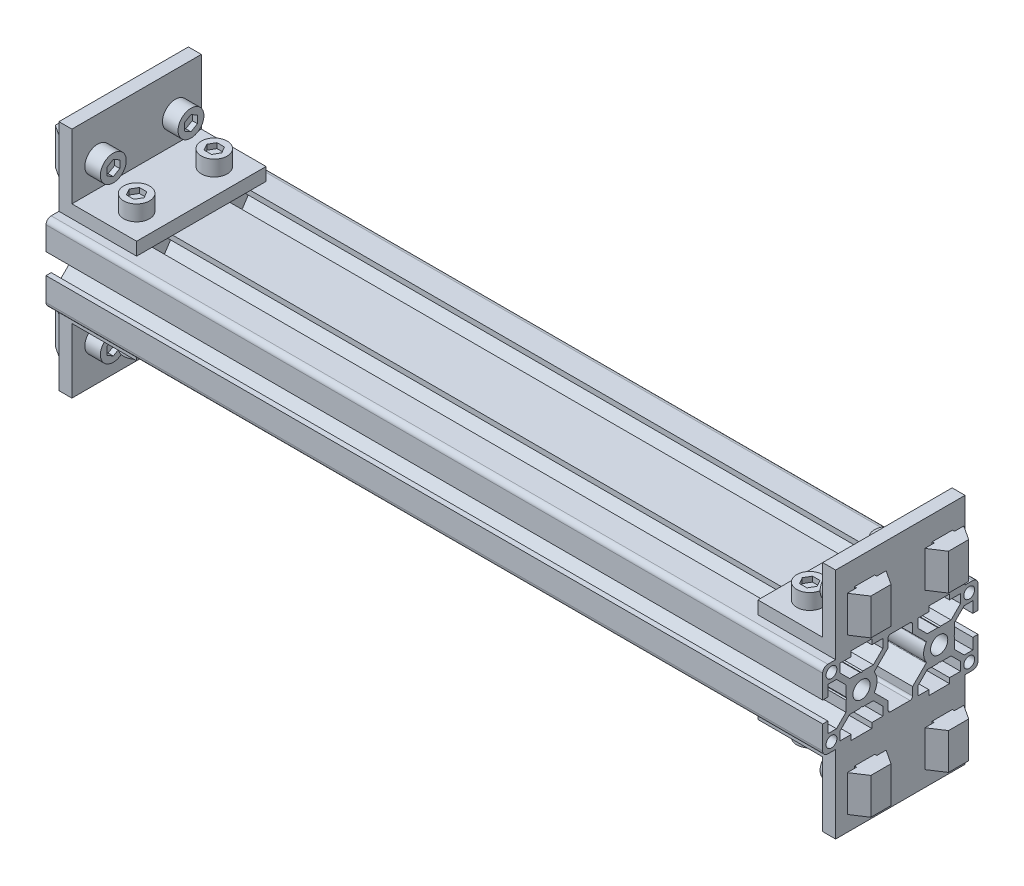
SolidWorks part; units mm, degrees
ref_plane "Front Plane" through (0, 0, 0) normal (0, 0, 1) x (1, 0, 0)
ref_plane "Top Plane" through (0, 0, 0) normal (0, 1, 0) x (1, 0, 0)
ref_plane "Right Plane" through (0, 0, 0) normal (1, 0, 0) x (0, 0, -1)
ref_plane "Plane1" through (300, 0, 0) normal (1, 0, 0) x (0, 0, -1)
ref_plane "Plane2" through (150, 0, 0) normal (1, 0, 0) x (0, 0, -1)
sketch "Sketch1" plane through (0, 0, 0) normal (1, 0, 0) x (0, 0, -1)
  line L0 (4.75, 8.8358) -> (4.75, 12)
  line L1 (3.75, 13) -> (-3.75, 13)
  line L2 (-4.75, 12) -> (-4.75, 8.8358)
  line L3 (-4.75, 8.8358) -> (-9.934, 3.6518)
  line L4 (-9.934, -3.6518) -> (-4.75, -8.8358)
  line L5 (-4.75, -8.8358) -> (-4.75, -12)
  line L6 (-3.75, -13) -> (3.75, -13)
  line L7 (4.75, -12) -> (4.75, -8.8358)
  line L8 (4.75, -8.8358) -> (9.934, -3.6518)
  line L9 (9.934, 3.6518) -> (4.75, 8.8358)
  line L10 (-11, -15) -> (11, -15)
  line L11 (11, -15) -> (11, -13)
  line L12 (11, -13) -> (6.75, -13)
  line L13 (6.75, -13) -> (6.75, -9.6642)
  line L14 (6.75, -9.6642) -> (10.4142, -6)
  line L15 (10.4142, -6) -> (14.4804, -6)
  line L16 (14.4804, -6) -> (15, -5.7)
  line L17 (15, -5.7) -> (15.5196, -6)
  line L18 (15.5196, -6) -> (19.5858, -6)
  line L19 (19.5858, -6) -> (23.25, -9.6642)
  line L20 (23.25, -9.6642) -> (23.25, -13)
  line L21 (23.25, -13) -> (19, -13)
  line L22 (19, -13) -> (19, -15)
  line L23 (19, -15) -> (28, -15)
  line L24 (30, -13) -> (30, -4)
  line L25 (30, -4) -> (28, -4)
  line L26 (28, -4) -> (28, -8.25)
  line L27 (28, -8.25) -> (24.6642, -8.25)
  line L28 (24.6642, -8.25) -> (21, -4.5858)
  line L29 (21, -4.5858) -> (21, -0.5196)
  line L30 (21, -0.5196) -> (20.7, 0)
  line L31 (20.7, 0) -> (21, 0.5196)
  line L32 (21, 0.5196) -> (21, 4.5858)
  line L33 (21, 4.5858) -> (24.6642, 8.25)
  line L34 (24.6642, 8.25) -> (28, 8.25)
  line L35 (28, 8.25) -> (28, 4)
  line L36 (28, 4) -> (30, 4)
  line L37 (30, 4) -> (30, 13)
  line L38 (28, 15) -> (19, 15)
  line L39 (19, 15) -> (19, 13)
  line L40 (19, 13) -> (23.25, 13)
  line L41 (23.25, 13) -> (23.25, 9.6642)
  line L42 (23.25, 9.6642) -> (19.5858, 6)
  line L43 (19.5858, 6) -> (15.5196, 6)
  line L44 (15.5196, 6) -> (15, 5.7)
  line L45 (15, 5.7) -> (14.4804, 6)
  line L46 (14.4804, 6) -> (10.4142, 6)
  line L47 (10.4142, 6) -> (6.75, 9.6642)
  line L48 (6.75, 9.6642) -> (6.75, 13)
  line L49 (6.75, 13) -> (11, 13)
  line L50 (11, 13) -> (11, 15)
  line L51 (11, 15) -> (-11, 15)
  line L52 (-11, 15) -> (-11, 13)
  line L53 (-11, 13) -> (-6.75, 13)
  line L54 (-6.75, 13) -> (-6.75, 9.6642)
  line L55 (-6.75, 9.6642) -> (-10.4142, 6)
  line L56 (-10.4142, 6) -> (-14.4804, 6)
  line L57 (-14.4804, 6) -> (-15, 5.7)
  line L58 (-15, 5.7) -> (-15.5196, 6)
  line L59 (-15.5196, 6) -> (-19.5858, 6)
  line L60 (-19.5858, 6) -> (-23.25, 9.6642)
  line L61 (-23.25, 9.6642) -> (-23.25, 13)
  line L62 (-23.25, 13) -> (-19, 13)
  line L63 (-19, 13) -> (-19, 15)
  line L64 (-19, 15) -> (-28, 15)
  line L65 (-30, 13) -> (-30, 4)
  line L66 (-30, 4) -> (-28, 4)
  line L67 (-28, 4) -> (-28, 8.25)
  line L68 (-28, 8.25) -> (-24.6642, 8.25)
  line L69 (-24.6642, 8.25) -> (-21, 4.5858)
  line L70 (-21, 4.5858) -> (-21, 0.5196)
  line L71 (-21, 0.5196) -> (-20.7, 0)
  line L72 (-20.7, 0) -> (-21, -0.5196)
  line L73 (-21, -0.5196) -> (-21, -4.5858)
  line L74 (-21, -4.5858) -> (-24.6642, -8.25)
  line L75 (-24.6642, -8.25) -> (-28, -8.25)
  line L76 (-28, -8.25) -> (-28, -4)
  line L77 (-28, -4) -> (-30, -4)
  line L78 (-30, -4) -> (-30, -13)
  line L79 (-28, -15) -> (-19, -15)
  line L80 (-19, -15) -> (-19, -13)
  line L81 (-19, -13) -> (-23.25, -13)
  line L82 (-23.25, -13) -> (-23.25, -9.6642)
  line L83 (-23.25, -9.6642) -> (-19.5858, -6)
  line L84 (-19.5858, -6) -> (-15.5196, -6)
  line L85 (-15.5196, -6) -> (-15, -5.7)
  line L86 (-15, -5.7) -> (-14.4804, -6)
  line L87 (-14.4804, -6) -> (-10.4142, -6)
  line L88 (-10.4142, -6) -> (-6.75, -9.6642)
  line L89 (-6.75, -9.6642) -> (-6.75, -13)
  line L90 (-6.75, -13) -> (-11, -13)
  line L91 (-11, -13) -> (-11, -15)
  line L92 (0, 15) -> (0, -15) construction
  arc A0 (28, -15) -> (30, -13) centre (28, -13) ccw
  arc A1 (30, 13) -> (28, 15) centre (28, 13) ccw
  arc A2 (-28, 15) -> (-30, 13) centre (-28, 13) ccw
  arc A3 (-30, -13) -> (-28, -15) centre (-28, -13) ccw
  circle A4 centre (-26.6, -11.6) radius 2.1
  circle A5 centre (-26.6, 11.6) radius 2.1
  circle A6 centre (-15, 0) radius 3.3235
  circle A7 centre (26.6, -11.6) radius 2.1
  circle A8 centre (15, 0) radius 3.3235
  circle A9 centre (26.6, 11.6) radius 2.1
  arc A10 (4.75, 12) -> (3.75, 13) centre (3.75, 12) ccw
  arc A11 (-3.75, 13) -> (-4.75, 12) centre (-3.75, 12) ccw
  arc A12 (-9.934, 3.6518) -> (-9.9732, 3.2759) centre (-9.7219, 3.4397) ccw
  arc A13 (-9.9732, -3.2759) -> (-9.9732, 3.2759) centre (-15, 0) ccw
  arc A14 (-9.9732, -3.2759) -> (-9.934, -3.6518) centre (-9.7219, -3.4397) ccw
  arc A15 (-4.75, -12) -> (-3.75, -13) centre (-3.75, -12) ccw
  arc A16 (3.75, -13) -> (4.75, -12) centre (3.75, -12) ccw
  arc A17 (9.934, -3.6518) -> (9.9732, -3.2759) centre (9.7219, -3.4397) ccw
  arc A18 (9.9732, 3.2759) -> (9.9732, -3.2759) centre (15, 0) ccw
  arc A19 (9.9732, 3.2759) -> (9.934, 3.6518) centre (9.7219, 3.4397) ccw
  point P106 (0, 0)
extrude "Boss-Extrude1" add sketch "Sketch1" along normal up to surface (300 mm away) up to plane "Plane1"
sketch "Sketch2" plane through (0, 0, 0) normal (0, 0, 1) x (1, 0, 0)
  line L0 (0, 45) -> (0, 15)
  line L1 (0, 15) -> (30, 15)
  line L2 (30, 15) -> (30, 20)
  line L3 (30, 20) -> (5, 20)
  line L4 (5, 20) -> (5, 45)
  line L5 (5, 45) -> (0, 45)
  line L6 (0, -16.5) -> (0, 16.5) construction
  dimension "FIX_1" = 30
  dimension "FIX_2" = 5
extrude "Boss-Extrude2" add sketch "Sketch2" along normal mid plane 50
ref_plane "Plane3" through (20, 0, 0) normal (1, 0, 0) x (0, 0, -1)
sketch "Sketch3" plane through (20, 0, 0) normal (1, 0, 0) x (0, 0, -1)
  line L0 (-15, 26) -> (-15, 8) construction
  line L1 (-19, 13) -> (-19, 15) construction
  line L2 (-11, 15) -> (-11, 13) construction
  line L3 (-15, 26) -> (-10, 26)
  line L4 (-10, 26) -> (-10, 20)
  line L5 (-10, 20) -> (-12, 20)
  line L6 (-12, 20) -> (-12, 8)
  line L7 (-12, 8) -> (-15, 8)
  line L8 (-15, 8) -> (-15, 26)
  dimension "FIX_7" = 6
  dimension "FIX_5" = 12
  dimension "FIX_8" = 10
  dimension "FIX_6" = 6
revolve "Revolve1" add sketch "Sketch3" angle 360 about L0
sketch "Sketch4" plane through (0, 26, 0) normal (0, 1, 0) x (1, 0, 0)
  line L0 (20, -12) -> (20, -15) construction
  line L1 (22.8868, -15) -> (21.4434, -12.5)
  line L2 (21.4434, -12.5) -> (18.5566, -12.5)
  line L3 (18.5566, -12.5) -> (17.1132, -15)
  line L4 (17.1132, -15) -> (18.5566, -17.5)
  line L5 (18.5566, -17.5) -> (21.4434, -17.5)
  line L6 (21.4434, -17.5) -> (22.8868, -15)
  line L7 (-33, 0) -> (33, 0) construction
  circle A0 centre (20, -15) radius 2.5 construction
  dimension "FIX_10" = 5
extrude "Cut-Extrude1" cut sketch "Sketch4" against normal blind 2
sketch "Sketch5" plane through (20, 0, 0) normal (1, 0, 0) x (0, 0, -1)
  line L0 (-18.9, 13.8) -> (-11.1, 13.8)
  line L1 (-11.1, 13.8) -> (-11.1, 13)
  line L2 (-11.1, 13) -> (-7.5, 13)
  line L3 (-7.5, 13) -> (-11.1, 7.5)
  line L4 (-11.1, 7.5) -> (-18.9, 7.5)
  line L5 (-18.9, 7.5) -> (-22.5, 13)
  line L6 (-22.5, 13) -> (-18.9, 13)
  line L7 (-18.9, 13) -> (-18.9, 13.8)
  line L8 (-15, 8) -> (-15, 26) construction
  line L9 (-19, 15) -> (-28, 15) construction
  dimension "FIX_12" = 1.2
  dimension "FIX_13" = 6.3
  dimension "FIX_14" = 0.8
  dimension "FIX_15" = 7.8
  dimension "FIX_16" = 15
extrude "Boss-Extrude3" add sketch "Sketch5" along normal mid plane 14
ref_plane "Plane4" through (0, 30, 0) normal (0, 1, 0) x (1, 0, 0)
sketch "Sketch6" plane through (0, 30, 0) normal (0, 1, 0) x (1, 0, 0)
  line L0 (-7, -15) -> (20, -15) construction
  line L1 (-33, 0) -> (33, 0) construction
  line L2 (-7, -12) -> (5, -12)
  line L3 (5, -12) -> (5, -10)
  line L4 (5, -10) -> (11, -10)
  line L5 (11, -10) -> (11, -15)
  line L6 (11, -15) -> (-7, -15)
  line L7 (-7, -15) -> (-7, -12)
  dimension "FIX_21" = 6
  dimension "FIX_19" = 12
  dimension "FIX_20" = 6
  dimension "FIX_22" = 10
revolve "Revolve2" add sketch "Sketch6" angle 360 about L0
sketch "Sketch7" plane through (11, 0, 0) normal (1, 0, 0) x (0, 0, -1)
  line L0 (0, 33) -> (0, -33) construction
  line L1 (-15, 32.8868) -> (-17.5, 31.4434)
  line L2 (-17.5, 31.4434) -> (-17.5, 28.5566)
  line L3 (-17.5, 28.5566) -> (-15, 27.1132)
  line L4 (-15, 27.1132) -> (-12.5, 28.5566)
  line L5 (-12.5, 28.5566) -> (-12.5, 31.4434)
  line L6 (-12.5, 31.4434) -> (-15, 32.8868)
  circle A0 centre (-15, 30) radius 2.5 construction
  dimension "FIX_24" = 5
extrude "Cut-Extrude2" cut sketch "Sketch7" against normal blind 2
sketch "Sketch8" plane through (0, 30, 0) normal (0, 1, 0) x (1, 0, 0)
  line L0 (11, -15) -> (-7, -15) construction
  line L1 (11, -20) -> (11, -10) construction
  line L2 (-2, -7.5) -> (-7.5, -11.1)
  line L3 (-7.5, -11.1) -> (-7.5, -18.9)
  line L4 (-7.5, -18.9) -> (-2, -22.5)
  line L5 (-2, -22.5) -> (-2, -18.9)
  line L6 (-2, -18.9) -> (-1.2, -18.9)
  line L7 (-1.2, -18.9) -> (-1.2, -11.1)
  line L8 (-1.2, -11.1) -> (-2, -11.1)
  line L9 (-2, -11.1) -> (-2, -7.5)
  line L11 (0, -33) -> (0, 33) construction
  dimension "FIX_27" = 6.3
  dimension "FIX_28" = 0.8
  dimension "FIX_29" = 7.8
  dimension "FIX_30" = 15
  dimension "FIX_31" = 1.2
extrude "Boss-Extrude4" add sketch "Sketch8" along normal mid plane 14
mirror "Mirror1" about plane through (0, 0, 0) normal (0, 0, 1) of "Boss-Extrude4", "Cut-Extrude2", "Revolve2", "Boss-Extrude3", "Cut-Extrude1", "Revolve1"
mirror "Mirror2" about plane through (0, 0, 0) normal (0, 1, 0) of "Boss-Extrude4", "Cut-Extrude2", "Revolve2", "Boss-Extrude3", "Cut-Extrude1", "Revolve1", "Boss-Extrude2", "Mirror1"
mirror "Mirror3" about plane through (150, 0, 0) normal (1, 0, 0) of "Boss-Extrude2", "Cut-Extrude2", "Mirror1", "Mirror2", "Revolve1", "Cut-Extrude1", "Boss-Extrude3", "Revolve2", "Boss-Extrude4"
ref_plane "Plane5" through (-15, 0, 0) normal (1, 0, 0) x (0, 0, -1)
ref_plane "Plane6" through (315, 0, 0) normal (1, 0, 0) x (0, 0, -1)
